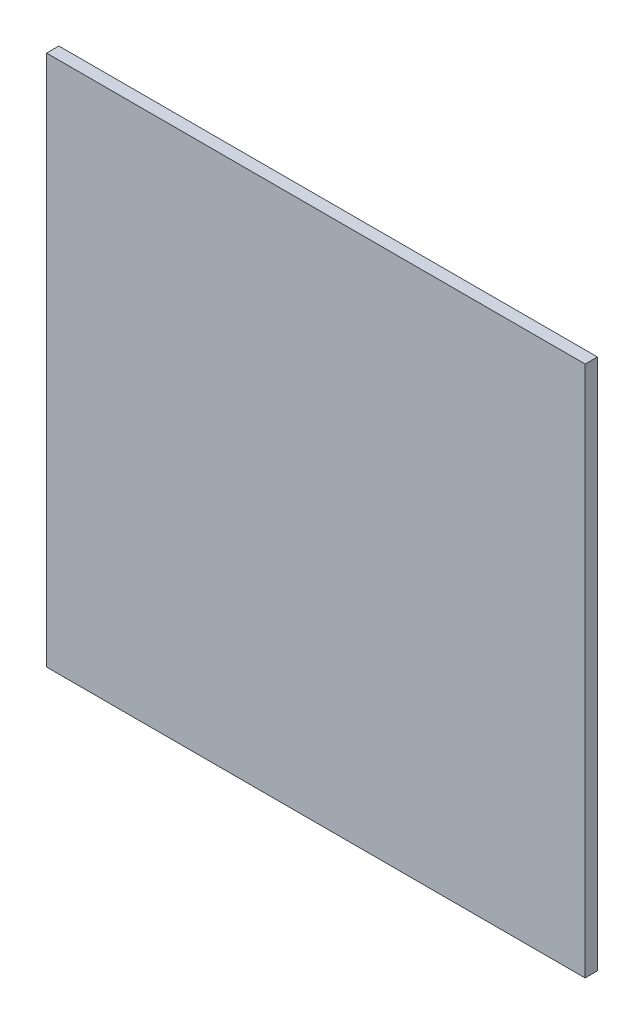
SolidWorks part; units mm, degrees
ref_plane "Front Plane" through (0, 0, 0) normal (0, 0, 1) x (1, 0, 0)
ref_plane "Top Plane" through (0, 0, 0) normal (0, 1, 0) x (1, 0, 0)
ref_plane "Right Plane" through (0, 0, 0) normal (1, 0, 0) x (0, 0, -1)
sketch "Sketch1" plane through (0, 0, 0) normal (0, 0, 1) x (1, 0, 0)
  line L1 (-28.6061, 15.0849) -> (366.3939, 15.0849)
  line L2 (-28.6061, 15.0849) -> (-28.6061, -374.9151)
  line L3 (-28.6061, -374.9151) -> (366.3939, -374.9151)
  line L4 (366.3939, 15.0849) -> (366.3939, -374.9151)
  dimension "D1" = 390
  dimension "D2" = 395
extrude "Boss-Extrude1" add sketch "Sketch1" along normal blind 9
